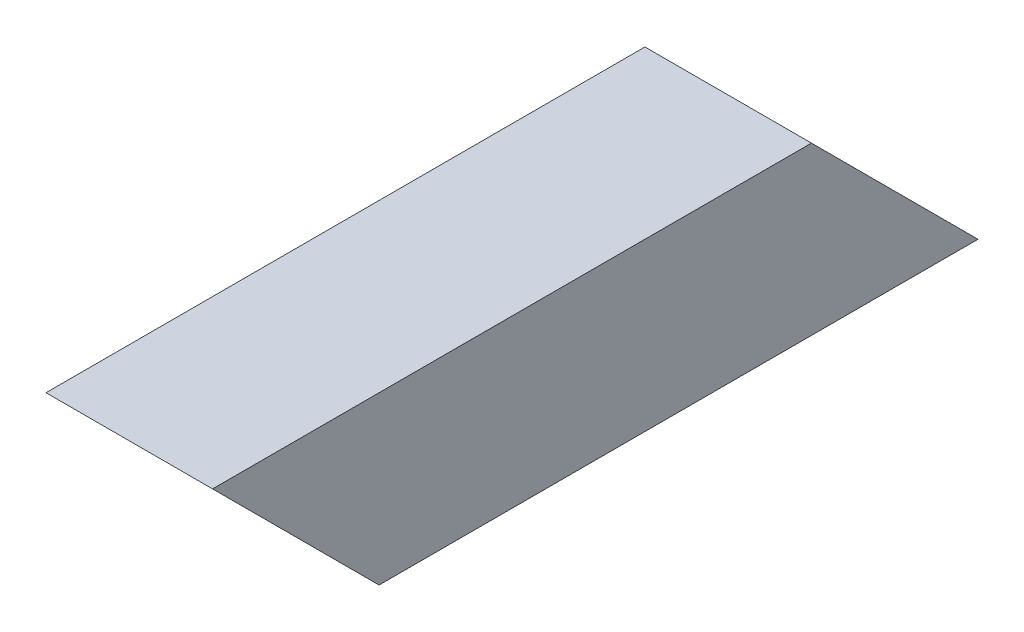
SolidWorks part; units mm, degrees
ref_plane "Front Plane" through (0, 0, 0) normal (0, 0, 1) x (1, 0, 0)
ref_plane "Top Plane" through (0, 0, 0) normal (0, 1, 0) x (1, 0, 0)
ref_plane "Right Plane" through (0, 0, 0) normal (1, 0, 0) x (0, 0, -1)
sketch "Sketch1" plane through (0, 0, 0) normal (0, 0, 1) x (1, 0, 0)
  line L1 (0, 0) -> (-25.4, 0)
  line L2 (0, 0) -> (0, 25.4)
  line L3 (0, 25.4) -> (-25.4, 25.4)
  line L4 (-25.4, 0) -> (-25.4, 25.4)
  line L5 (-3.175, 3.175) -> (-22.225, 3.175)
  line L6 (-3.175, 3.175) -> (-3.175, 22.225)
  line L7 (-3.175, 22.225) -> (-22.225, 22.225)
  line L8 (-22.225, 3.175) -> (-22.225, 22.225)
  dimension "D1" = 25.4
  dimension "D2" = 25.4
  dimension "D3" = 3.175
  dimension "D4" = 3.175
  dimension "D5" = 3.175
  dimension "D6" = 3.175
extrude "Boss-Extrude1" add sketch "Sketch1" along normal blind 116.7433
sketch "Sketch2" plane through (0, 0, 0) normal (1, 0, 0) x (0, 0, -1)
  line L0 (-116.7433, 25.4) -> (-91.3433, 0)
  line L1 (-116.7433, 0) -> (0, 0) construction
  line L2 (-91.3433, 0) -> (-116.7433, 0)
  line L3 (-116.7433, 0) -> (-116.7433, 25.4)
  line L7 (0, 0) -> (-25.4, 25.4)
  line L8 (-116.7433, 25.4) -> (0, 25.4) construction
  line L9 (-25.4, 25.4) -> (0, 25.4)
  line L10 (0, 25.4) -> (0, 0)
extrude "Cut-Extrude1" cut sketch "Sketch2" against normal through all
